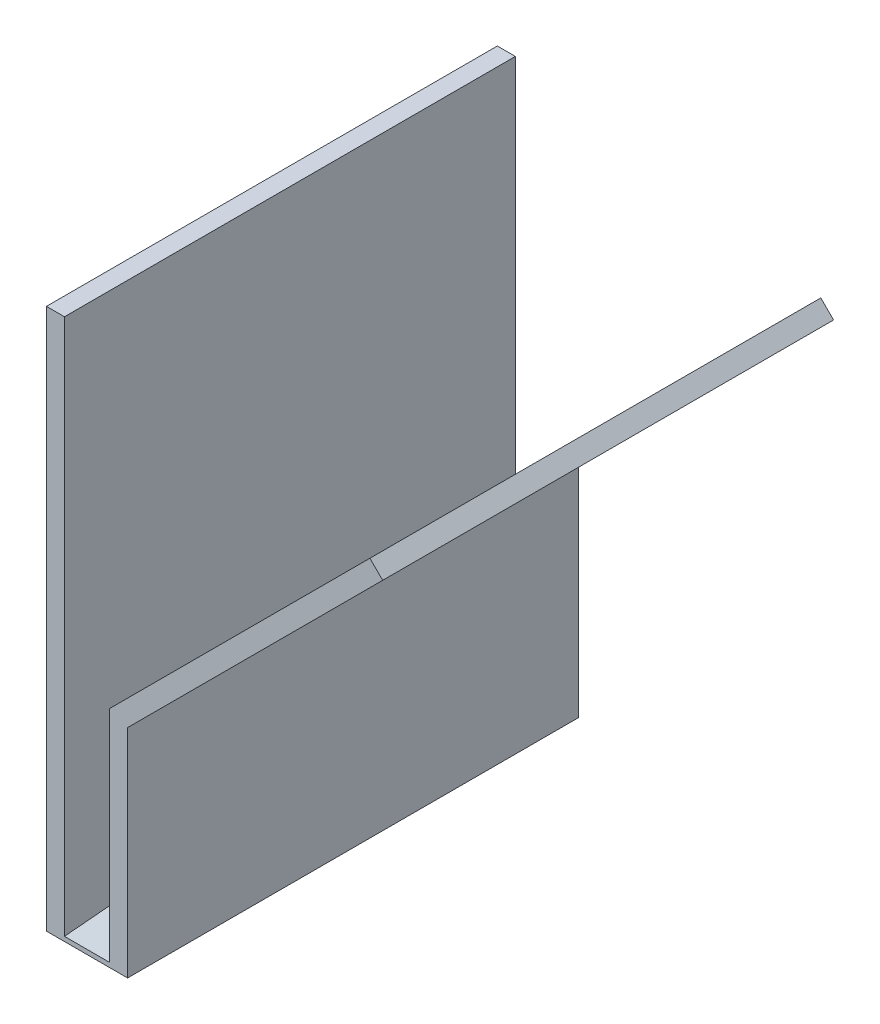
SolidWorks part; units mm, degrees
ref_plane "Front Plane" through (0, 0, 0) normal (0, 0, 1) x (1, 0, 0)
ref_plane "Top Plane" through (0, 0, 0) normal (0, 1, 0) x (1, 0, 0)
ref_plane "Right Plane" through (0, 0, 0) normal (1, 0, 0) x (0, 0, -1)
sketch "Sketch1" plane through (0, 0, 0) normal (0, 0, 1) x (1, 0, 0)
  line L1 (0, 0) -> (4, 0)
  line L2 (0, 0) -> (0, 120)
  line L3 (0, 120) -> (4, 120)
  line L4 (4, 0) -> (4, 120)
  dimension "D1" = 120
  dimension "D2" = 4
extrude "Boss-Extrude1" add sketch "Sketch1" along normal blind 100
sketch "Sketch2" plane through (4, 0, 0) normal (1, 0, 0) x (0, 0, -1)
  line L0 (-100, 0) -> (-100, 1)
  line L1 (-100, 0) -> (-100, 120) construction
  line L2 (-100, 1) -> (0, 9.7489)
  line L3 (0, 0) -> (0, 120) construction
  line L4 (0, 9.7489) -> (0, 0)
  line L5 (0, 0) -> (-100, 0)
  dimension "D1" = 1
  dimension "D2" = 5
extrude "Boss-Extrude2" add sketch "Sketch2" along normal blind 10
sketch "Sketch4" plane through (0, 0, 0) normal (0, 0, -1) x (-1, 0, 0)
  line L0 (-14, 0) -> (-14, 49.7489)
  line L1 (-14, 49.7489) -> (-71.7401, 107.489)
  line L2 (-71.7401, 107.489) -> (-74.5685, 104.6606)
  line L3 (-74.5685, 104.6606) -> (-18, 48.092)
  line L4 (-18, 48.092) -> (-18, 0)
  line L5 (-18, 0) -> (-14, 0)
  line L6 (-14, 9.7489) -> (-4, 9.7489) construction
  dimension "D1" = 4
  dimension "D2" = 40
  dimension "D3" = 4
  dimension "D4" = 80
  dimension "D5" = 45
extrude "Boss-Extrude3" add sketch "Sketch4" against normal up to surface (100 mm away) up to face at (6, 40.3333, 100)
